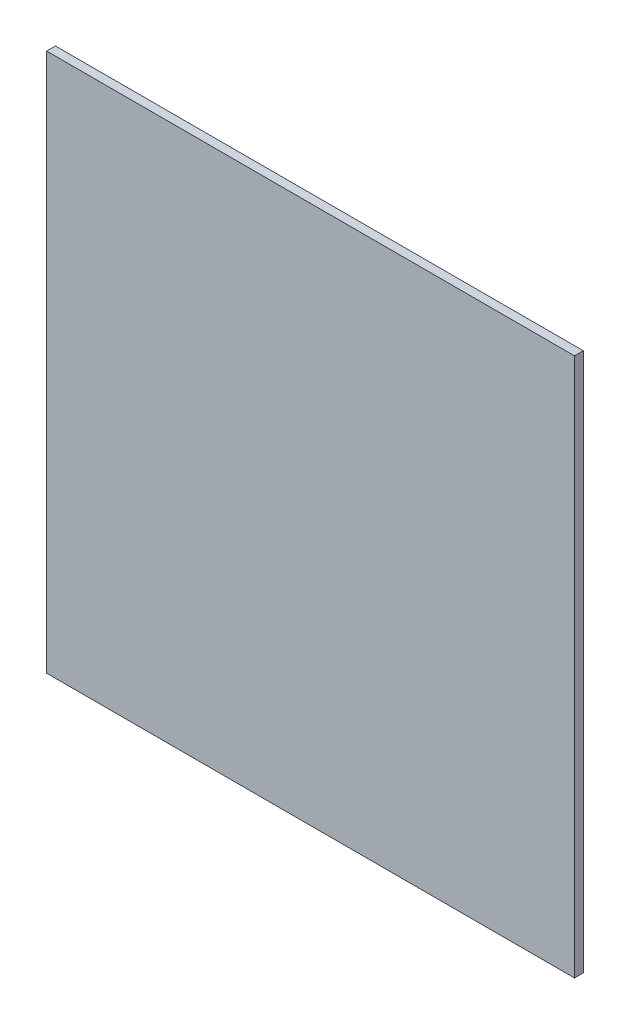
SolidWorks part; units mm, degrees
ref_plane "Ön Düzlem" through (0, 0, 0) normal (0, 0, 1) x (1, 0, 0)
ref_plane "Üst Düzlem" through (0, 0, 0) normal (0, 1, 0) x (1, 0, 0)
ref_plane "Sağ Düzlem" through (0, 0, 0) normal (1, 0, 0) x (0, 0, -1)
sketch "Sketch1" plane through (0, 0, 0) normal (0, 0, 1) x (1, 0, 0)
  line L1 (-240, 245) -> (240, 245)
  line L2 (-240, 245) -> (-240, -245)
  line L3 (-240, -245) -> (240, -245)
  line L4 (240, 245) -> (240, -245)
  line L5 (-240, 245) -> (240, -245) construction
  line L6 (-240, -245) -> (240, 245) construction
  point P0 (0, 0)
  dimension "D1" = 480
  dimension "D2" = 490
extrude "Boss-Extrude1" add sketch "Sketch1" along normal blind 8
